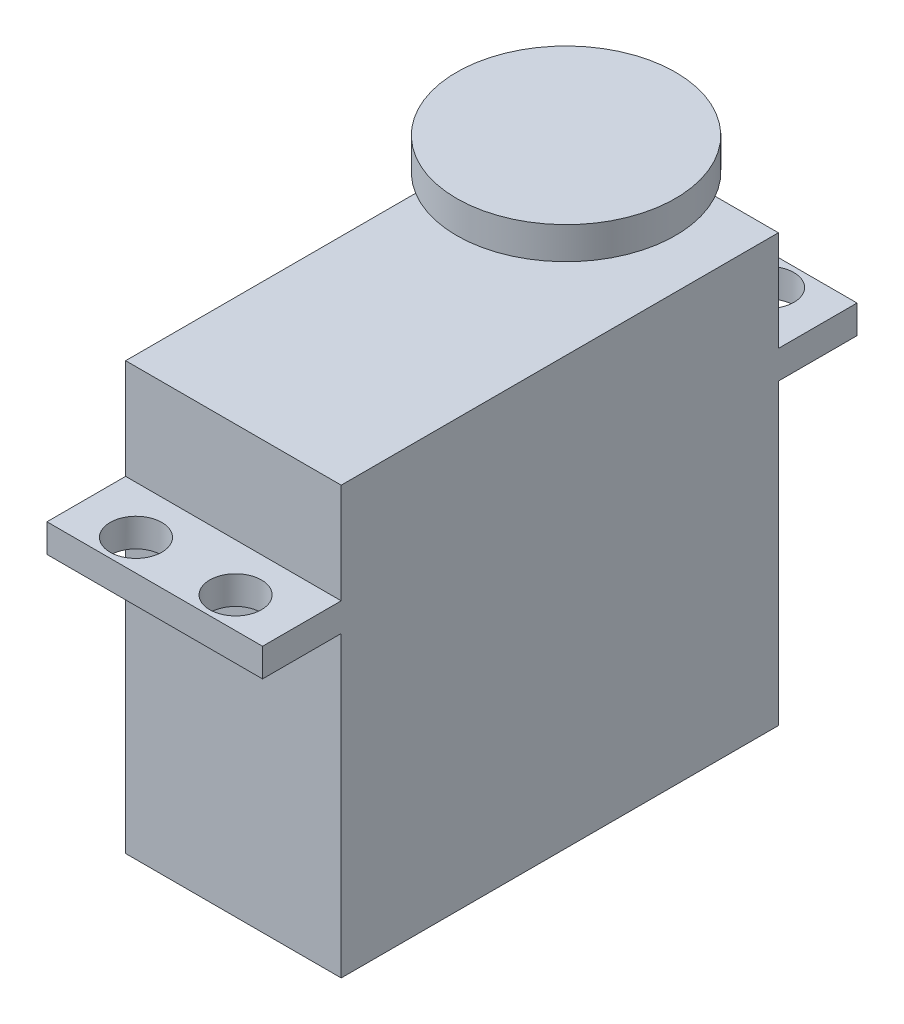
SolidWorks part; units mm, degrees
ref_plane "Front Plane" through (0, 0, 0) normal (0, 0, 1) x (1, 0, 0)
ref_plane "Top Plane" through (0, 0, 0) normal (0, 1, 0) x (1, 0, 0)
ref_plane "Right Plane" through (0, 0, 0) normal (1, 0, 0) x (0, 0, -1)
sketch "Sketch1" plane through (0, 0, 0) normal (0, 1, 0) x (1, 0, 0)
  line L1 (-9.9, 20.075) -> (9.9, 20.075)
  line L2 (-9.9, 20.075) -> (-9.9, -20.075)
  line L3 (-9.9, -20.075) -> (9.9, -20.075)
  line L4 (9.9, 20.075) -> (9.9, -20.075)
  line L5 (-9.9, 20.075) -> (9.9, -20.075) construction
  line L6 (-9.9, -20.075) -> (9.9, 20.075) construction
  point P0 (0, 0)
  dimension "D1" = 40.15
  dimension "D2" = 19.8
extrude "Boss-Extrude1" add sketch "Sketch1" along normal blind 39.2
sketch "Sketch4" plane through (0, 0, -20.075) normal (0, 0, -1) x (-1, 0, 0)
  line L0 (-9.9, 30) -> (9.9, 30)
  line L1 (-9.9, 39.2) -> (-9.9, 0) construction
  line L2 (9.9, 39.2) -> (9.9, 0) construction
  line L3 (-9.9, 27.4) -> (9.9, 27.4)
  line L4 (-9.9, 27.4) -> (-9.9, 30)
  line L5 (9.9, 27.4) -> (9.9, 30)
  dimension "D1" = 30
  dimension "D2" = 2.6
extrude "Boss-Extrude2" add sketch "Sketch4" along normal blind 7.225
sketch "Sketch5" plane through (0, 30, 0) normal (0, 1, 0) x (1, 0, 0)
  line L1 (9.9, 27.3) -> (9.9, 20.075) construction
  line L3 (-9.9, 20.075) -> (9.9, 20.075) construction
  line L4 (-9.9, 27.3) -> (9.9, 27.3) construction
  line L5 (0, 27.3) -> (0, 20.075) construction
  line L6 (9.9, 20.075) -> (-9.9, 20.075) construction
  circle A0 centre (4.575, 24.45) radius 2.375
  circle A1 centre (-4.575, 24.45) radius 2.375
  dimension "D1" = 4.75
  dimension "D3" = 4.375
  dimension "D2" = 5.325
extrude "Cut-Extrude1" cut sketch "Sketch5" against normal up to next
mirror "Mirror2" about plane through (0, 0, 0) normal (0, 0, 1) of "Cut-Extrude1", "Boss-Extrude2"
sketch "Sketch6" plane through (0, 39.2, 0) normal (0, 1, 0) x (1, 0, 0)
  line L0 (9.9, 20.075) -> (-9.9, 20.075) construction
  line L1 (0, 20.075) -> (0, -20.075) construction
  line L2 (-9.9, -20.075) -> (9.9, -20.075) construction
  circle A0 centre (0, 10.475) radius 2.825
  dimension "D2" = 5.65
  dimension "D1" = 9.6
extrude "Boss-Extrude3" add sketch "Sketch6" along normal blind 4.65
sketch "Sketch8" plane through (0, 43.85, 0) normal (0, 1, 0) x (1, 0, 0)
  circle A0 centre (0, 10.475) radius 2.825 construction
  circle A1 centre (0, 10.475) radius 2.825 construction
  circle A2 centre (0, 10.475) radius 10.05
  dimension "D1" = 20.1
extrude "Boss-Extrude4" add sketch "Sketch8" along normal blind 2.95
